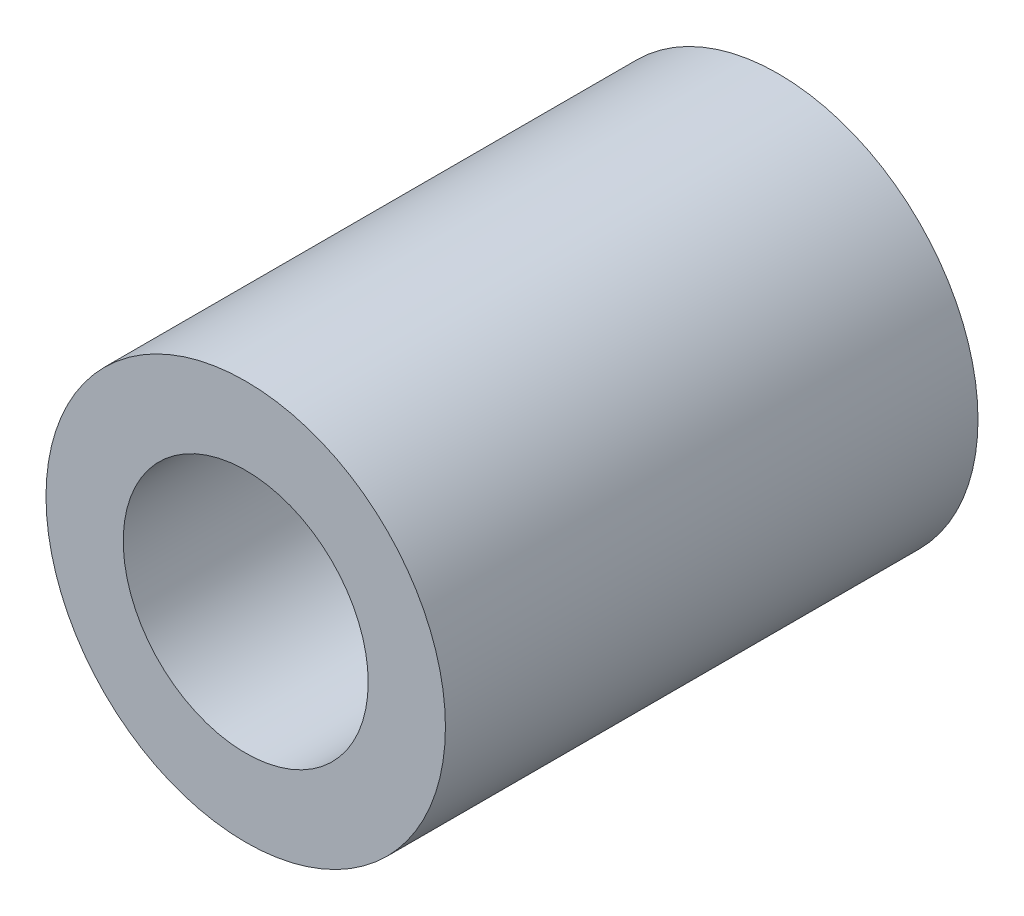
SolidWorks part; units mm, degrees
ref_plane "Front Plane" through (0, 0, 0) normal (0, 0, 1) x (1, 0, 0)
ref_plane "Top Plane" through (0, 0, 0) normal (0, 1, 0) x (1, 0, 0)
ref_plane "Right Plane" through (0, 0, 0) normal (1, 0, 0) x (0, 0, -1)
sketch "Sketch1" plane through (0, 0, 0) normal (0, 0, 1) x (1, 0, 0)
  circle A0 centre (0, 0) radius 2.3812
  circle A1 centre (0, 0) radius 1.4605
  dimension "OD" = 4.7625
  dimension "ID" = 2.921
extrude "Extrude1" add sketch "Sketch1" along normal mid plane 6.35
sketch "Sketch2" plane through (0, 0, 0) normal (1, 0, 0) x (0, 0, -1)
  line L0 (-3.175, -1.4605) -> (3.175, -1.4605) construction
  line L3 (3.175, 1.4605) -> (-3.175, 1.4605) construction
  line L5 (-3.175, -1.4605) -> (3.175, -1.4605)
  line L6 (3.175, 1.4605) -> (-3.175, 1.4605)
sketch "Sketch4" plane through (0, 0, 3.175) normal (0, 0, 1) x (1, 0, 0)
  line L0 (0, 0) -> (-1.0327, 1.0327)
  line L1 (0, -2.6194) -> (0, 2.6194) construction
  circle A0 centre (0, 0) radius 1.4605 construction
  dimension "D1" = 45
